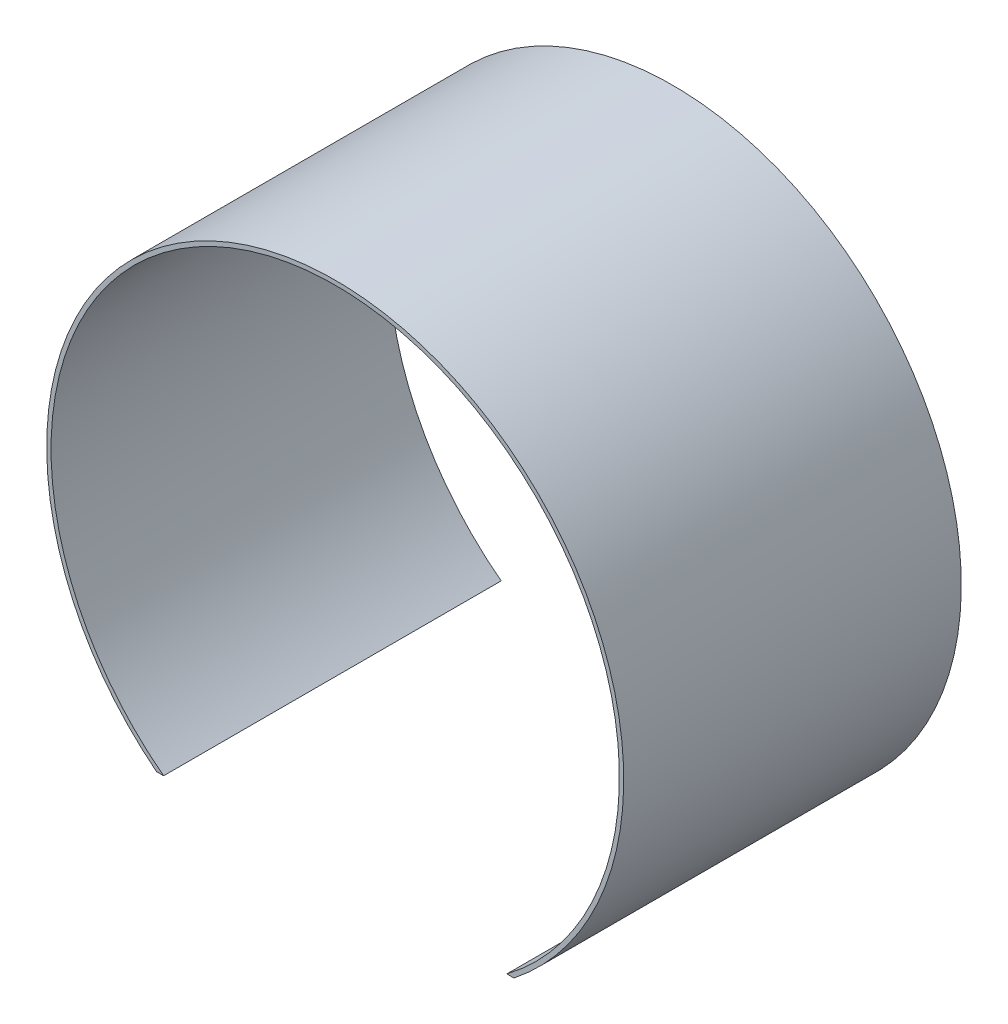
SolidWorks part; units mm, degrees
ref_plane "前视基准面" through (0, 0, 0) normal (0, 0, 1) x (1, 0, 0)
ref_plane "上视基准面" through (0, 0, 0) normal (0, 1, 0) x (1, 0, 0)
ref_plane "右视基准面" through (0, 0, 0) normal (1, 0, 0) x (0, 0, -1)
sketch "草图2" plane through (0, 0, 0) normal (0, 0, 1) x (1, 0, 0)
  line L0 (0, 0) -> (0, -78.5173) construction
  line L1 (-61.9276, -78.5173) -> (-59.475, -78.5173)
  line L5 (59.475, -78.5173) -> (61.9276, -78.5173)
  arc A4 (59.475, -78.5173) -> (-59.475, -78.5173) centre (0, 0) ccw
  arc A5 (61.9276, -78.5173) -> (-61.9276, -78.5173) centre (0, 0) ccw
  dimension "D1" = 197
  dimension "D2" = 200
  dimension "D3" = 90
extrude "凸台-拉伸1" add sketch "草图2" along normal blind 117
